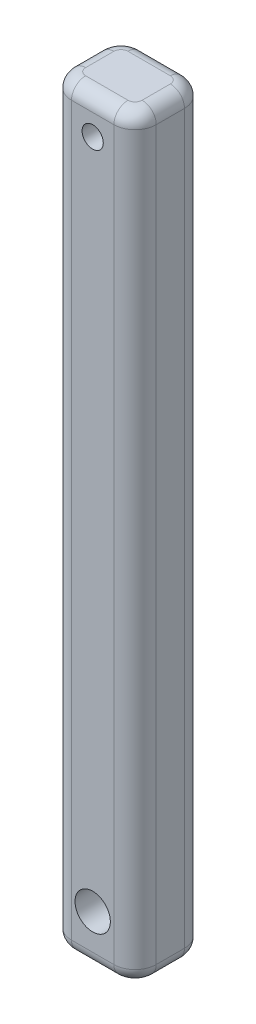
SolidWorks part; units mm, degrees
ref_plane "Front Plane" through (0, 0, 0) normal (0, 0, 1) x (1, 0, 0)
ref_plane "Top Plane" through (0, 0, 0) normal (0, 1, 0) x (1, 0, 0)
ref_plane "Right Plane" through (0, 0, 0) normal (1, 0, 0) x (0, 0, -1)
sketch "Sketch1" plane through (0, 0, 0) normal (0, 1, 0) x (1, 0, 0)
  line L1 (-7.62, 12.7) -> (7.62, 12.7)
  line L2 (-15.24, 5.08) -> (-15.24, -5.08)
  line L3 (-7.62, -12.7) -> (7.62, -12.7)
  line L4 (15.24, 5.08) -> (15.24, -5.08)
  line L5 (-15.24, 12.7) -> (15.24, -12.7) construction
  line L6 (-15.24, -12.7) -> (15.24, 12.7) construction
  arc A0 (-15.24, -5.08) -> (-7.62, -12.7) centre (-7.62, -5.08) ccw
  arc A1 (-7.62, 12.7) -> (-15.24, 5.08) centre (-7.62, 5.08) ccw
  arc A2 (7.62, 12.7) -> (15.24, 5.08) centre (7.62, 5.08) cw
  arc A3 (7.62, -12.7) -> (15.24, -5.08) centre (7.62, -5.08) ccw
  point P0 (0, 0)
  dimension "D3" = 7.62
  dimension "D1" = 30.48
  dimension "D2" = 25.4
extrude "Boss-Extrude1" add sketch "Sketch1" along normal blind 271.78
ref_plane "Plane1" through (0, 0, 12.7) normal (0, 0, 1) x (1, 0, 0)
sketch "Sketch2" plane through (0, 0, 12.7) normal (0, 0, 1) x (1, 0, 0)
  line L0 (0, 24.13) -> (0, 11.43) construction
  line L1 (-7.62, 0) -> (7.62, 0) construction
  circle A0 centre (0, 17.78) radius 6.35
  point P6 (0, 0)
  dimension "D1" = 12.7
  dimension "D2" = 17.78
extrude "Cut-Extrude1" cut sketch "Sketch2" against normal through all
sketch "Sketch3" plane through (0, 0, 12.7) normal (0, 0, 1) x (1, 0, 0)
  line L0 (-7.62, 271.78) -> (7.62, 271.78) construction
  circle A0 centre (0, 259.08) radius 3.81
  point P5 (0, 271.78)
  dimension "D1" = 7.62
  dimension "D2" = 12.7
extrude "Cut-Extrude2" cut sketch "Sketch3" against normal through all contours A0
fillet "Fillet1" radius 5.08 8 edges at (-15.24, 271.78, 0) (-13.0082, 271.78, -10.4682) (0, 271.78, -12.7) (13.0082, 271.78, -10.4682) (15.24, 271.78, 0) (13.0082, 271.78, 10.4682) (0, 271.78, 12.7) (-13.0082, 271.78, 10.4682)
fillet "Fillet2" radius 5.08 8 edges at (0, 0, 12.7) (13.0082, 0, 10.4682) (15.24, 0, 0) (13.0082, 0, -10.4682) (0, 0, -12.7) (-13.0082, 0, -10.4682) (-15.24, 0, 0) (-13.0082, 0, 10.4682)
